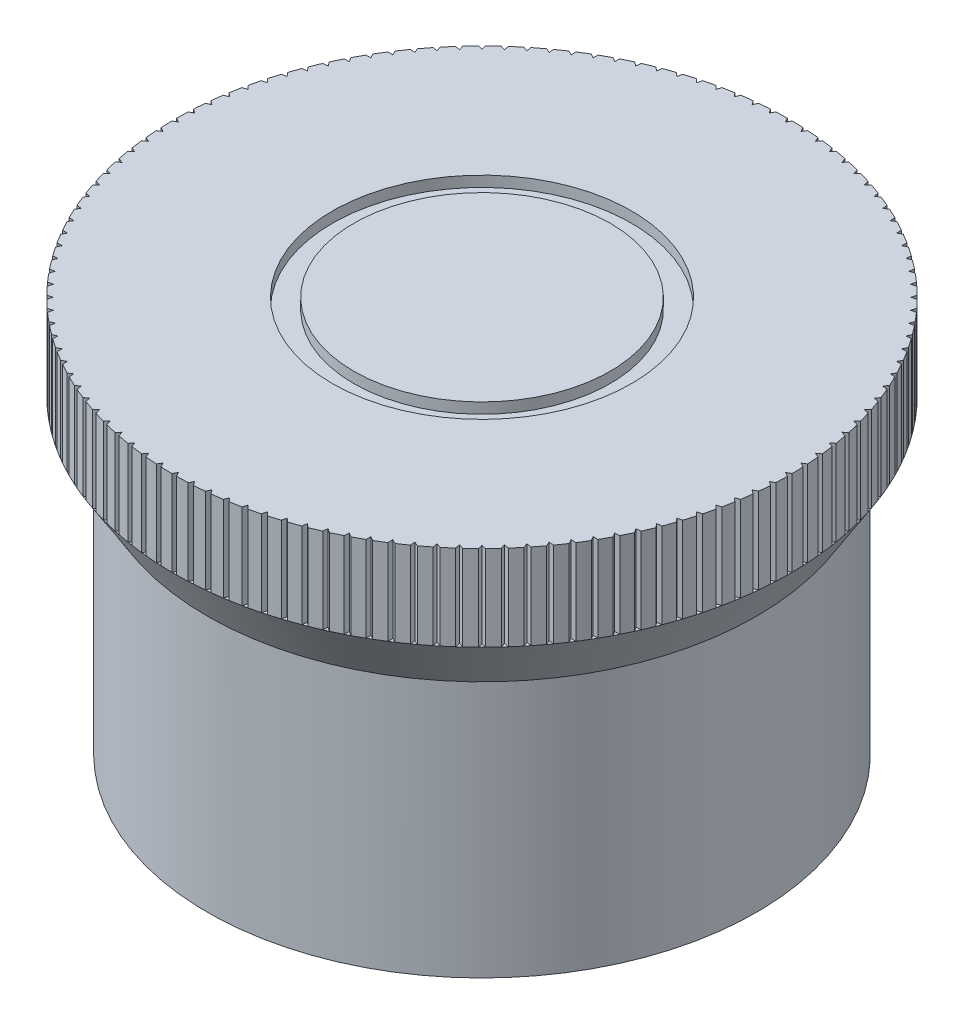
SolidWorks part; units mm, degrees
ref_plane "正面" through (0, 0, 0) normal (0, 0, 1) x (1, 0, 0)
ref_plane "平面" through (0, 0, 0) normal (0, 1, 0) x (1, 0, 0)
ref_plane "右側面" through (0, 0, 0) normal (1, 0, 0) x (0, 0, -1)
sketch "ｽｹｯﾁ1" plane through (0, 0, 0) normal (0, 1, 0) x (1, 0, 0)
  circle A0 centre (0, 0) radius 14.4
  dimension "D1" = 28.8
extrude "ﾎﾞｽ - 押し出し1" add sketch "ｽｹｯﾁ1" along normal blind 4
sketch "ｽｹｯﾁ3" plane through (0, 4, 0) normal (0, 1, 0) x (1, 0, 0)
  line L0 (-14.3995, 0.1152) -> (-14.2, 0)
  line L1 (-14.2, 0) -> (-14.3995, -0.1152)
  line L2 (0, 0) -> (-50000, 0) construction
  circle A1 centre (0, 0) radius 14.4 construction
  arc A2 (-14.3995, 0.1152) -> (-14.3995, -0.1152) centre (0, 0) ccw
  dimension "D1" = 30
  dimension "D2" = 14.2
extrude "ｶｯﾄ - 押し出し1" cut sketch "ｽｹｯﾁ3" against normal through all
pattern_circular "円形ﾊﾟﾀｰﾝ1" count 120 over 360 about axis through (0, 0, 0) along (0, 1, 0) of "ｶｯﾄ - 押し出し1"
sketch "ｽｹｯﾁ8" plane through (0, 4, 0) normal (0, 1, 0) x (1, 0, 0)
  circle A0 centre (0, 0) radius 7
  circle A1 centre (0, 0) radius 6
  dimension "D1" = 12
  dimension "D2" = 14
extrude "ｶｯﾄ - 押し出し2" cut sketch "ｽｹｯﾁ8" against normal blind 0.5
ref_plane "平面2" through (0, -2.5, 0) normal (0, 1, 0) x (-1, 0, 0)
sketch "ｽｹｯﾁ9" plane through (0, -2.5, 0) normal (0, 1, 0) x (-1, 0, 0)
  circle A0 centre (0, 0) radius 12.85
  dimension "D1" = 25.7
sketch "ｽｹｯﾁ10" plane through (0, 0, 0) normal (0, -1, 0) x (1, 0, 0)
  circle A0 centre (0, 0) radius 14.4
loft "ﾛﾌﾄ2" add profiles "ｽｹｯﾁ10", "ｽｹｯﾁ9"
sketch "ｽｹｯﾁ11" plane through (0, -2.5, 0) normal (0, -1, 0) x (1, 0, 0)
  circle A0 centre (0, 0) radius 12.85
  dimension "D1" = 25.7
extrude "ﾎﾞｽ - 押し出し2" add sketch "ｽｹｯﾁ11" along normal blind 12
